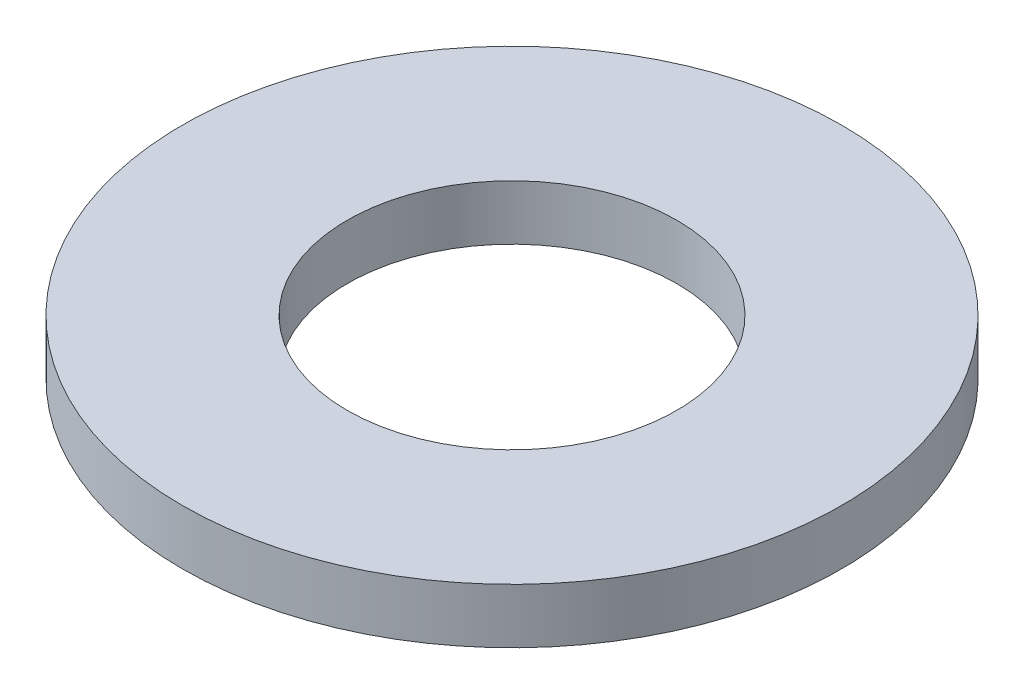
SolidWorks part; units mm, degrees
ref_plane "Front Plane" through (0, 0, 0) normal (0, 0, 1) x (1, 0, 0)
ref_plane "Top Plane" through (0, 0, 0) normal (0, 1, 0) x (1, 0, 0)
ref_plane "Right Plane" through (0, 0, 0) normal (1, 0, 0) x (0, 0, -1)
sketch "Sketch1" plane through (0, 0, 0) normal (0, 1, 0) x (1, 0, 0)
  circle A0 centre (0, 0) radius 9.525
  circle A1 centre (0, 0) radius 19.05
  dimension "D1" = 38.1
  dimension "D2" = 19.05
extrude "Boss-Extrude1" add sketch "Sketch1" along normal blind 3.175
